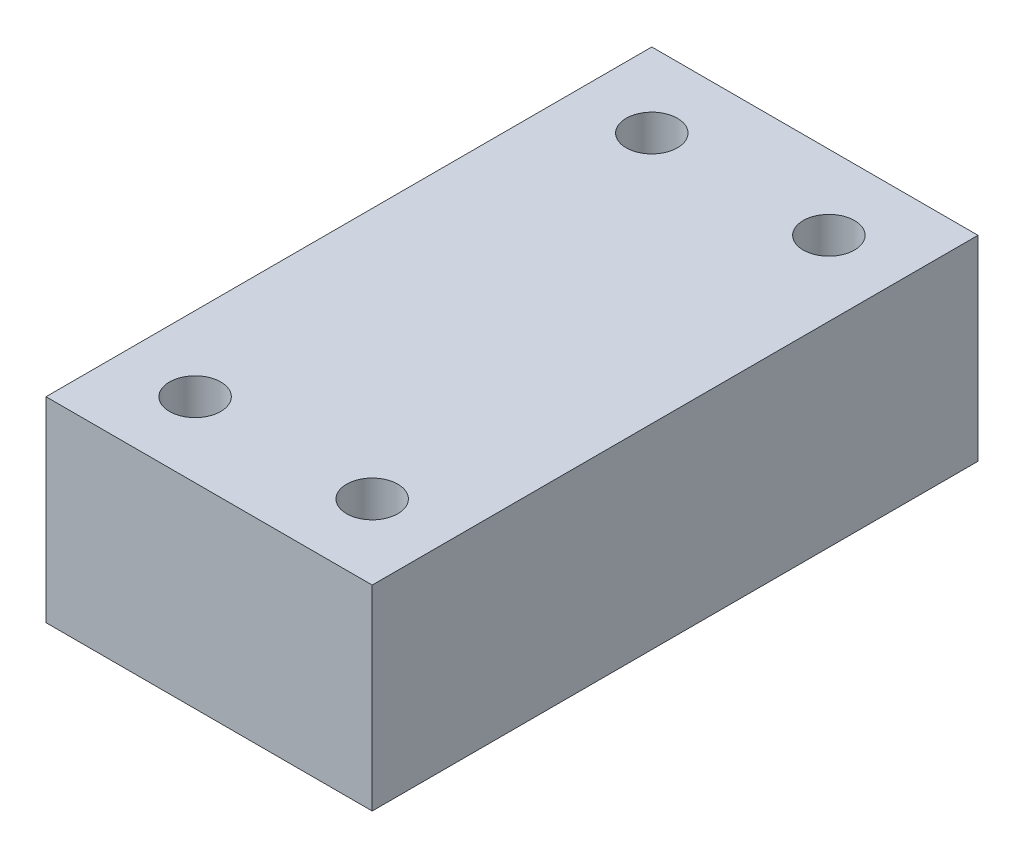
SolidWorks part; units mm, degrees
ref_plane "Ebene vorne" through (0, 0, 0) normal (0, 0, 1) x (1, 0, 0)
ref_plane "Ebene oben" through (0, 0, 0) normal (0, 1, 0) x (1, 0, 0)
ref_plane "Ebene rechts" through (0, 0, 0) normal (1, 0, 0) x (0, 0, -1)
sketch "Skizze1" plane through (0, 0, 0) normal (0, 1, 0) x (1, 0, 0)
  line L0 (-17.5, 0) -> (17.5, 0) construction
  line L1 (-17.5, 32.5) -> (17.5, 32.5)
  line L2 (-17.5, 32.5) -> (-17.5, -32.5)
  line L3 (-17.5, -32.5) -> (17.5, -32.5)
  line L4 (17.5, 32.5) -> (17.5, -32.5)
  line L5 (0, 32.5) -> (0, -32.5) construction
  point P8 (0, 0)
  dimension "D1" = 65
  dimension "D2" = 35
extrude "Aufsatz-Linear austragen1" add sketch "Skizze1" along normal blind 21
hole_wizard "Durchgangsloch für M51" positions "Skizze2" profile "Skizze3" hole size "M5" standard "DIN" end condition through all
sketch "Skizze2" plane through (78.1259, 21, -61.7446) normal (0, 1, 0) x (1, 0, 0)
  point P0 (-68.6259, -37.2446)
  point P1 (-87.6259, -37.2446)
  point P2 (-87.6259, -86.2446)
  point P3 (-68.6259, -86.2446)
sketch "Skizze3" plane through (9.5, 21, -24.5) normal (1, 0, 0) x (0, 0, 1)
  line L0 (0, 0) -> (0, 21)
  line L1 (0, 21) -> (2.75, 21)
  line L2 (2.75, 21) -> (2.75, 0)
  line L5 (2.75, 0) -> (0, 0)
  line L11 (0, -6.35) -> (0, 107.95) construction
  dimension "Bohrerdurchmesser" = 5.5
  dimension "Bohrungstiefe" = 21
